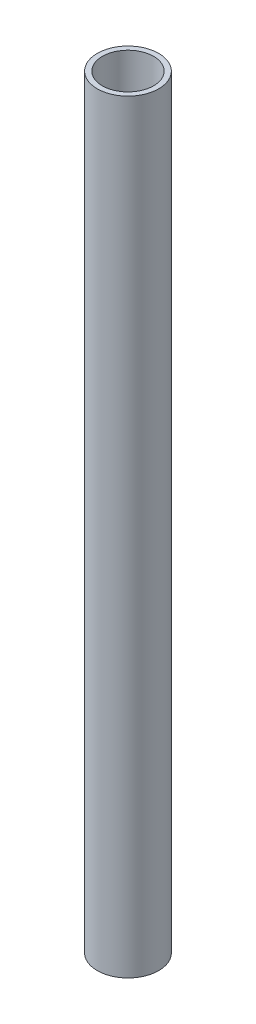
SolidWorks part; units mm, degrees
ref_plane "Спереди" through (0, 0, 0) normal (0, 0, 1) x (1, 0, 0)
ref_plane "Сверху" through (0, 0, 0) normal (0, 1, 0) x (1, 0, 0)
ref_plane "Справа" through (0, 0, 0) normal (1, 0, 0) x (0, 0, -1)
sketch "Эскиз1" plane through (0, 0, 0) normal (0, 1, 0) x (1, 0, 0)
  circle A0 centre (0, 0) radius 12.5
  circle A1 centre (0, 0) radius 15
extrude "Вытянуть1" add sketch "Эскиз1" along normal blind 373
